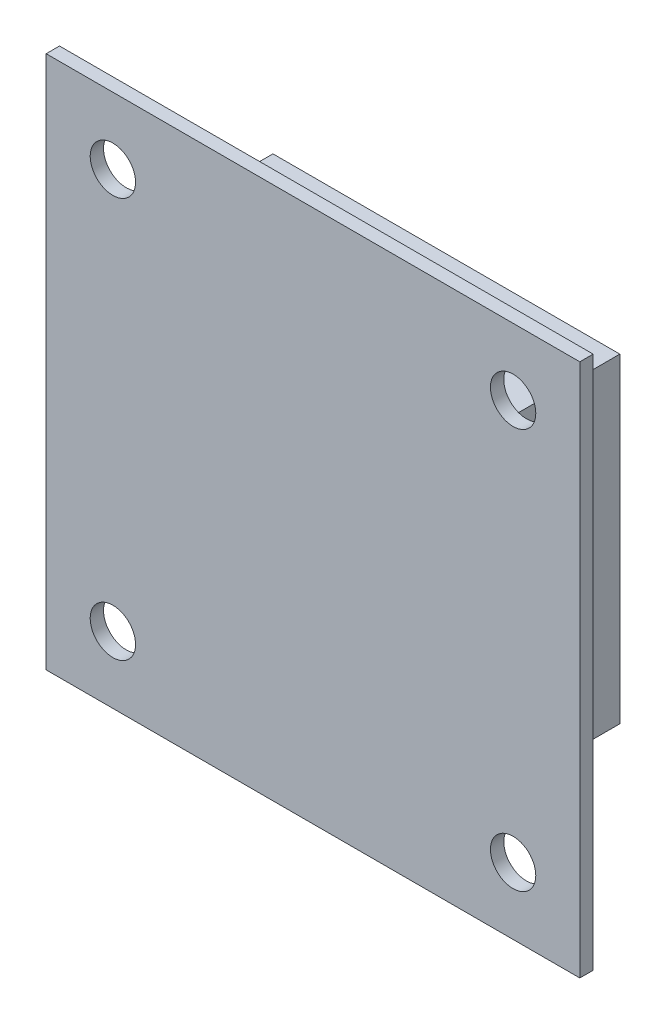
SolidWorks part; units mm, degrees
ref_plane "Front Plane" through (0, 0, 0) normal (0, 0, 1) x (1, 0, 0)
ref_plane "Top Plane" through (0, 0, 0) normal (0, 1, 0) x (1, 0, 0)
ref_plane "Right Plane" through (0, 0, 0) normal (1, 0, 0) x (0, 0, -1)
sketch "Sketch1" plane through (0, 0, 0) normal (0, 0, 1) x (1, 0, 0)
  line L1 (-20, -20) -> (20, -20)
  line L2 (-20, -20) -> (-20, 20)
  line L3 (-20, 20) -> (20, 20)
  line L4 (20, -20) -> (20, 20)
  line L5 (-20, -20) -> (20, 20) construction
  line L6 (-20, 20) -> (20, -20) construction
  point P0 (0, 0)
extrude "Boss-Extrude1" add sketch "Sketch1" against normal blind 1
ref_plane "Plane_1" through (0, 0, 0) normal (0, 0, 1) x (1, 0, 0)
sketch "Sketch2" plane through (0, 0, 0) normal (0, 0, 1) x (1, 0, 0)
  line L1 (-13, -12) -> (13, -12)
  line L2 (-13, -12) -> (-13, 12)
  line L3 (-13, 12) -> (13, 12)
  line L4 (13, -12) -> (13, 12)
  line L5 (-13, -12) -> (13, 12) construction
  line L6 (-13, 12) -> (13, -12) construction
  point P0 (0, 0)
extrude "Boss-Extrude2" add sketch "Sketch2" against normal blind 10
sketch "Sketch3" plane through (0, 0, 0) normal (0, 0, 1) x (1, 0, 0)
  circle A0 centre (-15, -15) radius 1.7
  circle A1 centre (-15, 15) radius 1.7
  circle A2 centre (15, -15) radius 1.7
  circle A3 centre (15, 15) radius 1.7
extrude "Lo_M3_bat_driver" cut sketch "Sketch3" along normal through all and the other way through all
